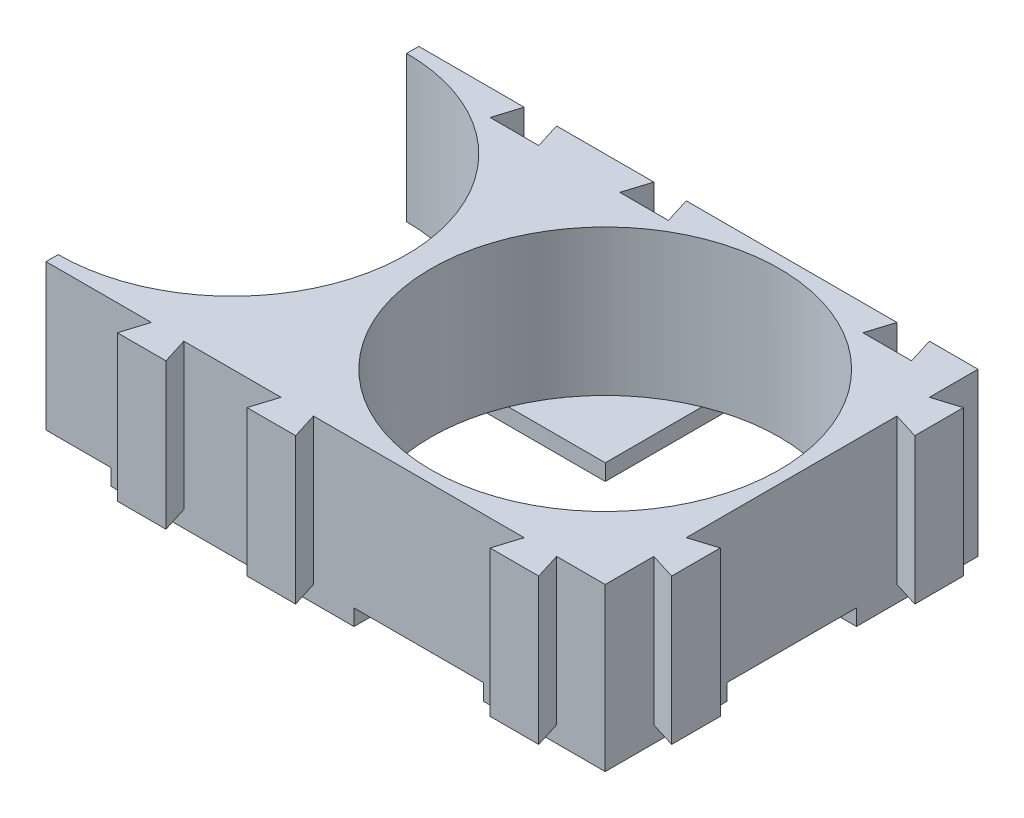
SolidWorks part; units mm, degrees
ref_plane "Front Plane" through (0, 0, 0) normal (0, 0, 1) x (1, 0, 0)
ref_plane "Top Plane" through (0, 0, 0) normal (0, 1, 0) x (1, 0, 0)
ref_plane "Right Plane" through (0, 0, 0) normal (1, 0, 0) x (0, 0, -1)
sketch "Sketch1" plane through (0, 0, 0) normal (0, 1, 0) x (1, 0, 0)
  line L1 (0, 0) -> (47.6, 0)
  line L2 (0, 0) -> (0, 24.6)
  line L3 (0, 24.6) -> (47.6, 24.6)
  line L4 (47.6, 0) -> (47.6, 24.6)
  dimension "D1" = 47.6
  dimension "D2" = 24.6
extrude "Boss-Extrude1" add sketch "Sketch1" along normal blind 10
sketch "Sketch2" plane through (0, 10, 0) normal (0, 1, 0) x (1, 0, 0)
  line L0 (0, -5.5) -> (0, 5.5) construction
  line L1 (47.6, 0) -> (47.6, 24.6) construction
  line L3 (47.6, 24.6) -> (0, 24.6) construction
  circle A0 centre (11.5, 13.1) radius 10.75
  circle A1 centre (34.5, 13.1) radius 10.75
  dimension "D1" = 21.5
  dimension "D2" = 21.5
  dimension "D3" = 23
  dimension "D4" = 11.5
  dimension "D5" = 13.1
  dimension "D6" = 11.5
extrude "Cut-Extrude1" cut sketch "Sketch2" against normal blind 9
sketch "Sketch3" plane through (0, 10, 0) normal (0, 1, 0) x (1, 0, 0)
  line L0 (0, 24.6) -> (0, -11.4) construction
  line L1 (0, -5.5) -> (0, 5.5) construction
  line L2 (47.6, 24.6) -> (0, 24.6) construction
  line L9 (3, 24.6) -> (2.5, 23)
  line L10 (2.5, 23) -> (5.5, 23)
  line L11 (5.5, 23) -> (5, 24.6)
  line L12 (5, 24.6) -> (3, 24.6)
  line L13 (18, 24.6) -> (17.5, 23)
  line L14 (17.5, 23) -> (20.5, 23)
  line L15 (20.5, 23) -> (20, 24.6)
  line L16 (20, 24.6) -> (18, 24.6)
  line L17 (26, 24.6) -> (25.5, 23)
  line L18 (25.5, 23) -> (28.5, 23)
  line L19 (28.5, 23) -> (28, 24.6)
  line L20 (28, 24.6) -> (26, 24.6)
  line L21 (41, 24.6) -> (40.5, 23)
  line L22 (40.5, 23) -> (43.5, 23)
  line L23 (43.5, 23) -> (43, 24.6)
  line L24 (43, 24.6) -> (41, 24.6)
  line L25 (0, 21.6) -> (1.6, 22.1)
  line L26 (1.6, 22.1) -> (1.6, 19.1)
  line L27 (1.6, 19.1) -> (0, 19.6)
  line L28 (0, 19.6) -> (0, 21.6)
  line L29 (0, 6.6) -> (1.6, 7.1)
  line L30 (1.6, 7.1) -> (1.6, 4.1)
  line L31 (1.6, 4.1) -> (0, 4.6)
  line L32 (0, 4.6) -> (0, 6.6)
  dimension "D1" = 2
  dimension "D2" = 3
  dimension "D3" = 0.5
  dimension "D4" = 1.6
  dimension "D5" = 3
  dimension "D6" = 13
  dimension "D7" = 2
  dimension "D8" = 3
  dimension "D9" = 0.5
  dimension "D10" = 1.6
  dimension "D11" = 6
  dimension "D12" = 2
  dimension "D13" = 3
  dimension "D14" = 0.5
  dimension "D15" = 1.6
  dimension "D16" = 13
  dimension "D17" = 2
  dimension "D18" = 3
  dimension "D19" = 0.5
  dimension "D20" = 1.6
  dimension "D21" = 3
  dimension "D22" = 2
  dimension "D23" = 0.5
  dimension "D24" = 1.6
  dimension "D25" = 3
  dimension "D26" = 3
  dimension "D27" = 2
  dimension "D28" = 0.5
  dimension "D29" = 1.6
  dimension "D30" = 13
extrude "Cut-Extrude2" cut sketch "Sketch3" against normal blind 9
sketch "Sketch5" plane through (0, 10, 0) normal (0, 1, 0) x (1, 0, 0)
  line L0 (-5.5, 0) -> (5.5, 0) construction
  line L1 (47.6, 24.6) -> (46, 24.6)
  line L2 (47.6, 24.6) -> (47.6, 0)
  line L3 (47.6, 0) -> (46, 0)
  line L4 (46, 24.6) -> (46, 0)
  dimension "D1" = 1.6
extrude "Cut-Extrude3" cut sketch "Sketch5" against normal blind 10
sketch "Sketch6" plane through (0, 10, 0) normal (0, 1, 0) x (1, 0, 0)
  line L0 (46, 24.6) -> (46, 0) construction
  line L1 (0, 0) -> (46, 0)
  line L2 (0, 0) -> (0, 1.6)
  line L3 (0, 1.6) -> (46, 1.6)
  line L4 (46, 0) -> (46, 1.6)
  dimension "D1" = 1.6
extrude "Cut-Extrude4" cut sketch "Sketch6" against normal blind 10
sketch "Sketch7" plane through (0, 10, 0) normal (0, 1, 0) x (1, 0, 0)
  line L0 (46, 21.6) -> (47.6, 22.1)
  line L1 (46, 24.6) -> (46, 1.6) construction
  line L2 (47.6, 22.1) -> (47.6, 19.1)
  line L3 (47.6, 19.1) -> (46, 19.6)
  line L4 (46, 19.6) -> (46, 21.6)
  line L9 (46, 6.6) -> (47.6, 7.1)
  line L10 (47.6, 7.1) -> (47.6, 4.1)
  line L11 (47.6, 4.1) -> (46, 4.6)
  line L12 (46, 4.6) -> (46, 6.6)
  line L13 (3, 1.6) -> (2.5, 0)
  line L14 (46, 1.6) -> (0, 1.6) construction
  line L15 (-5.5, 0) -> (5.5, 0) construction
  line L16 (2.5, 0) -> (5.5, 0)
  line L17 (5.5, 0) -> (5, 1.6)
  line L18 (5, 1.6) -> (3, 1.6)
  line L19 (0, -5.5) -> (0, 5.5) construction
  line L20 (18, 1.6) -> (17.5, 0)
  line L21 (17.5, 0) -> (20.5, 0)
  line L22 (20.5, 0) -> (20, 1.6)
  line L23 (20, 1.6) -> (18, 1.6)
  line L24 (26, 1.6) -> (25.5, 0)
  line L25 (25.5, 0) -> (28.5, 0)
  line L26 (28.5, 0) -> (28, 1.6)
  line L27 (28, 1.6) -> (26, 1.6)
  line L28 (41, 1.6) -> (40.5, 0)
  line L29 (40.5, 0) -> (43.5, 0)
  line L30 (43.5, 0) -> (43, 1.6)
  line L31 (43, 1.6) -> (41, 1.6)
  dimension "D1" = 3
  dimension "D2" = 2
  dimension "D3" = 0.5
  dimension "D4" = 1.6
  dimension "D5" = 3
  dimension "D6" = 13
  dimension "D7" = 2
  dimension "D8" = 3
  dimension "D9" = 0.5
  dimension "D10" = 1.6
  dimension "D11" = 3
  dimension "D12" = 2
  dimension "D13" = 3
  dimension "D14" = 0.5
  dimension "D15" = 1.6
  dimension "D16" = 2
  dimension "D17" = 3
  dimension "D18" = 0.5
  dimension "D19" = 1.6
  dimension "D20" = 13
  dimension "D21" = 2
  dimension "D22" = 3
  dimension "D23" = 0.5
  dimension "D24" = 6
  dimension "D25" = 2
  dimension "D26" = 3
  dimension "D27" = 0.5
  dimension "D28" = 13
extrude "Boss-Extrude2" add sketch "Sketch7" against normal blind 9
sketch "Sketch10" plane through (0, 0, 0) normal (0, -1, 0) x (1, 0, 0)
  line L0 (0, -5.5) -> (0, 5.5) construction
  line L1 (0, -9.1) -> (46, -9.1)
  line L2 (0, -9.1) -> (0, -17.1039)
  line L3 (0, -17.1039) -> (46, -17.1039)
  line L4 (46, -9.1) -> (46, -17.1039)
  line L5 (46, -24.6) -> (46, -1.6) construction
  line L7 (46, -1.6) -> (0, -1.6) construction
  dimension "D1" = 8.0039
  dimension "D2" = 7.5
extrude "Cut-Extrude5" cut sketch "Sketch10" against normal blind 1
sketch "Sketch11" plane through (0, 0, 0) normal (0, -1, 0) x (1, 0, 0)
  line L0 (46, -1.6) -> (0, -1.6) construction
  line L1 (7.5, -1.6) -> (15.5, -1.6)
  line L2 (7.5, -1.6) -> (7.5, -24.6)
  line L3 (7.5, -24.6) -> (15.5, -24.6)
  line L4 (15.5, -1.6) -> (15.5, -24.6)
  line L5 (46, -24.6) -> (0, -24.6) construction
  line L6 (0, -5.5) -> (0, 5.5) construction
  line L8 (30.5, -1.6) -> (38.5, -1.6)
  line L9 (30.5, -1.6) -> (30.5, -24.6)
  line L10 (30.5, -24.6) -> (38.5, -24.6)
  line L11 (38.5, -1.6) -> (38.5, -24.6)
  dimension "D1" = 8
  dimension "D2" = 7.5
  dimension "D3" = 8
  dimension "D4" = 7.5
extrude "Cut-Extrude6" cut sketch "Sketch11" against normal blind 1
sketch "Sketch12" plane through (0, 10, 0) normal (0, 1, 0) x (1, 0, 0)
  line L0 (18, 24.6) -> (5, 24.6) construction
  line L1 (11.5, 24.6) -> (0, 24.6)
  line L2 (11.5, 24.6) -> (11.5, 0)
  line L3 (11.5, 0) -> (0, 0)
  line L4 (0, 24.6) -> (0, 0)
extrude "Cut-Extrude7" cut sketch "Sketch12" against normal blind 10
